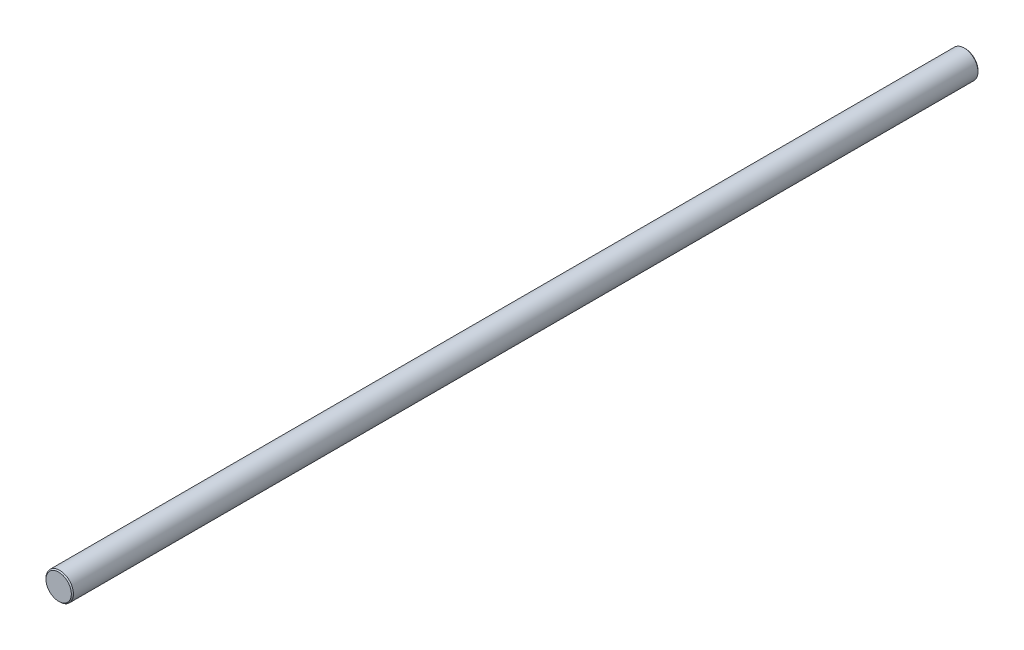
SolidWorks part; units mm, degrees
ref_plane "Front Plane" through (0, 0, 0) normal (0, 0, 1) x (1, 0, 0)
ref_plane "Top Plane" through (0, 0, 0) normal (0, 1, 0) x (1, 0, 0)
ref_plane "Right Plane" through (0, 0, 0) normal (1, 0, 0) x (0, 0, -1)
sketch "Sketch1" plane through (0, 0, 0) normal (0, 0, 1) x (1, 0, 0)
  circle A0 centre (0, 0) radius 10
  dimension "D1" = 20
extrude "Boss-Extrude1" add sketch "Sketch1" along normal mid plane 660.4
chamfer "Chamfer1" distance 0.762 angle 45 2 edges at (10, 0, -330.2) (10, 0, 330.2)
